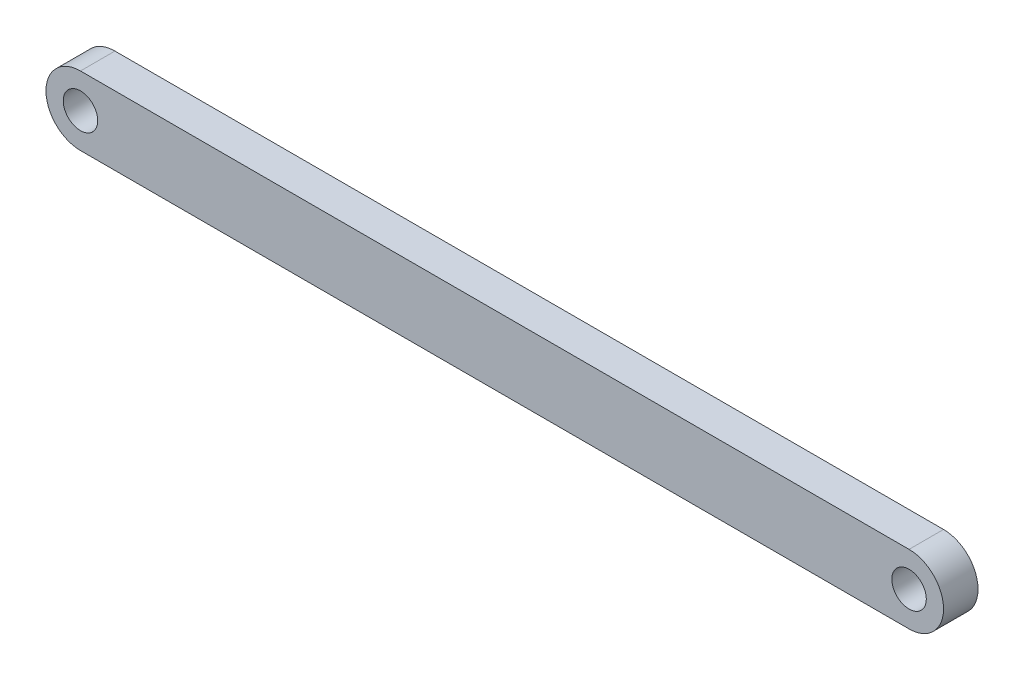
SolidWorks part; units mm, degrees
ref_plane "前基準面" through (0, 0, 0) normal (0, 0, 1) x (1, 0, 0)
ref_plane "上基準面" through (0, 0, 0) normal (0, 1, 0) x (1, 0, 0)
ref_plane "右基準面" through (0, 0, 0) normal (1, 0, 0) x (0, 0, -1)
sketch "草圖1" plane through (0, 0, 0) normal (0, 0, 1) x (1, 0, 0)
  line L0 (-24.04, 2.0012) -> (24.04, 2.0012)
  line L1 (-24.04, -1.9988) -> (24.04, -1.9988)
  arc A0 (-24.04, 2.0012) -> (-24.04, -1.9988) centre (-24.04, 0.0012) ccw
  arc A1 (24.04, -1.9988) -> (24.04, 2.0012) centre (24.04, 0.0012) ccw
  circle A2 centre (-24.04, 0.0012) radius 1
  circle A3 centre (24.04, 0.0012) radius 1
  dimension "D1" = 48.08
  dimension "D2" = 2
  dimension "D3" = 2
  dimension "D5" = 24.04
extrude "填料-伸長1" add sketch "草圖1" along normal blind 2
